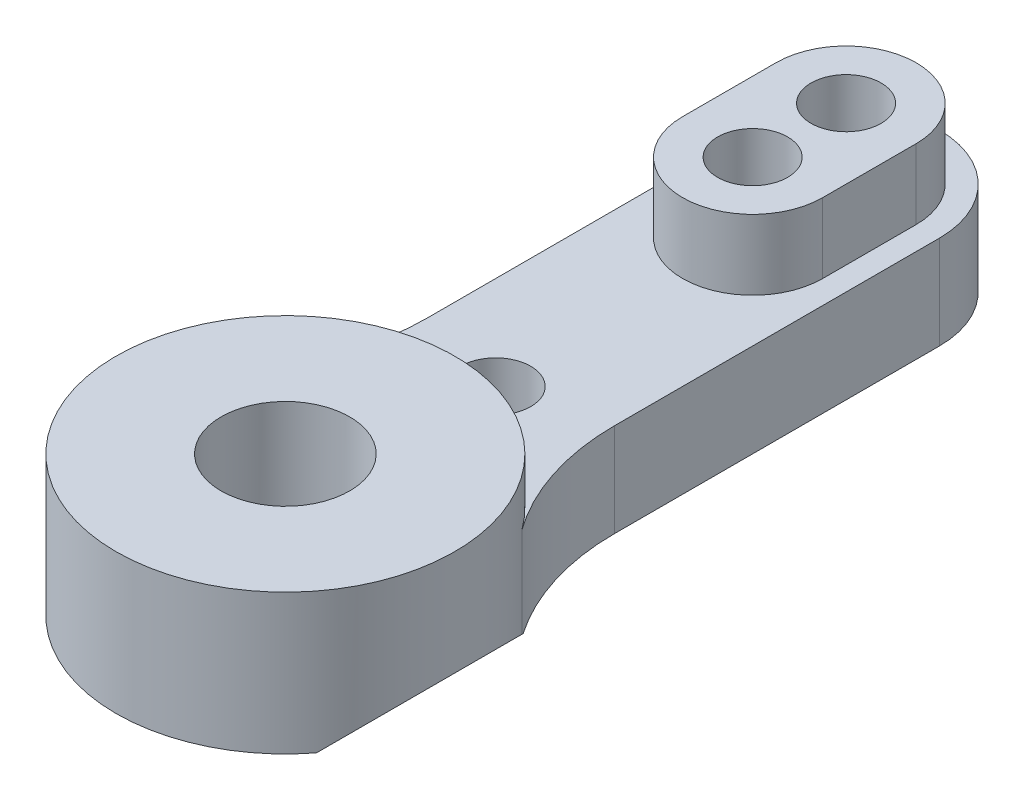
SolidWorks part; units mm, degrees
ref_plane "Front Plane" through (0, 0, 0) normal (0, 0, 1) x (1, 0, 0)
ref_plane "Top Plane" through (0, 0, 0) normal (0, 1, 0) x (1, 0, 0)
ref_plane "Right Plane" through (0, 0, 0) normal (1, 0, 0) x (0, 0, -1)
sketch "Sketch1" plane through (0, 0, 0) normal (0, 1, 0) x (1, 0, 0)
  line L0 (-4, -5.9533) -> (-4, 12)
  line L1 (4, 12) -> (4, -5.9533)
  line L2 (0, 12) -> (0, -12) construction
  arc A0 (-4, 12) -> (4, 12) centre (0, 12) cw
  arc A3 (-4, -5.9533) -> (4, -5.9533) centre (0, -12) ccw
  point P5 (0, 0)
  dimension "D1" = 7.25
  dimension "D2" = 8
  dimension "D3" = 24
extrude "Boss-Extrude1" add sketch "Sketch1" along normal mid plane 4
sketch "Sketch2" plane through (0, 2, 0) normal (0, 1, 0) x (1, 0, 0)
  circle A0 centre (0, -12) radius 7.25
extrude "Boss-Extrude2" add sketch "Sketch2" along normal blind 2
sketch "Sketch3" plane through (0, 2, 0) normal (0, 1, 0) x (1, 0, 0)
  line L0 (4, -5.9533) -> (4, 12) construction
  line L2 (-3, 12) -> (-3, 8)
  line L4 (3, 12) -> (3, 8)
  line L5 (-4, 12) -> (-4, -5.9533) construction
  arc A0 (-3, 12) -> (3, 12) centre (0, 12) cw
  arc A1 (-3, 8) -> (3, 8) centre (0, 8) ccw
  arc A2 (4, 12) -> (-4, 12) centre (0, 12) ccw construction
  point P13 (0, 16)
  point P14 (0, 15)
  point P15 (0, 5)
  dimension "D1" = 1
  dimension "D2" = 1
  dimension "D3" = 1
  dimension "D4" = 10
extrude "Boss-Extrude3" add sketch "Sketch3" along normal blind 3
sketch "Sketch4" plane through (0, 4, 0) normal (0, 1, 0) x (1, 0, 0)
  circle A0 centre (0, -12) radius 2.75
  dimension "D1" = 5.5
extrude "Cut-Extrude1" cut sketch "Sketch4" against normal through all
sketch "Sketch5" plane through (0, -2, 0) normal (0, -1, 0) x (1, 0, 0)
  circle A0 centre (0, 12) radius 4
extrude "Cut-Extrude2" cut sketch "Sketch5" against normal blind 1
sketch "Sketch6" plane through (0, -2, 0) normal (0, -1, 0) x (1, 0, 0)
  circle A0 centre (0, -12) radius 1.5
  circle A1 centre (0, -8) radius 1.5
  circle A2 centre (0, 3) radius 1.5
  circle A3 centre (0, 12) radius 2.75 construction
  dimension "D3" = 3
  dimension "D1" = 4
  dimension "D2" = 24
  dimension "D4" = 9
extrude "Cut-Extrude3" cut sketch "Sketch6" against normal through all
fillet "Fillet1" radius 10 2 edges at (-4, 0, 5.9533) (4, 0, 5.9533)
sketch "Sketch7" plane through (0, 0, 0) normal (0, 0, 1) x (1, 0, 0)
  line L0 (-7.25, -2) -> (-5.75, -2)
  line L1 (-7.25, -2) -> (7.25, -2) construction
  line L2 (-5.75, -2) -> (-7.25, -0.5)
  line L3 (-7.25, 4) -> (-7.25, -2) construction
  line L4 (-7.25, -0.5) -> (-7.25, -2)
  line L5 (7.25, -2) -> (5.75, -2)
  line L6 (5.75, -2) -> (7.25, -0.5)
  line L7 (7.25, -2) -> (7.25, 4) construction
  line L8 (7.25, -0.5) -> (7.25, -2)
  dimension "D1" = 1.5
  dimension "D2" = 1.5
extrude "Cut-Extrude4" cut sketch "Sketch7" along normal blind 18
